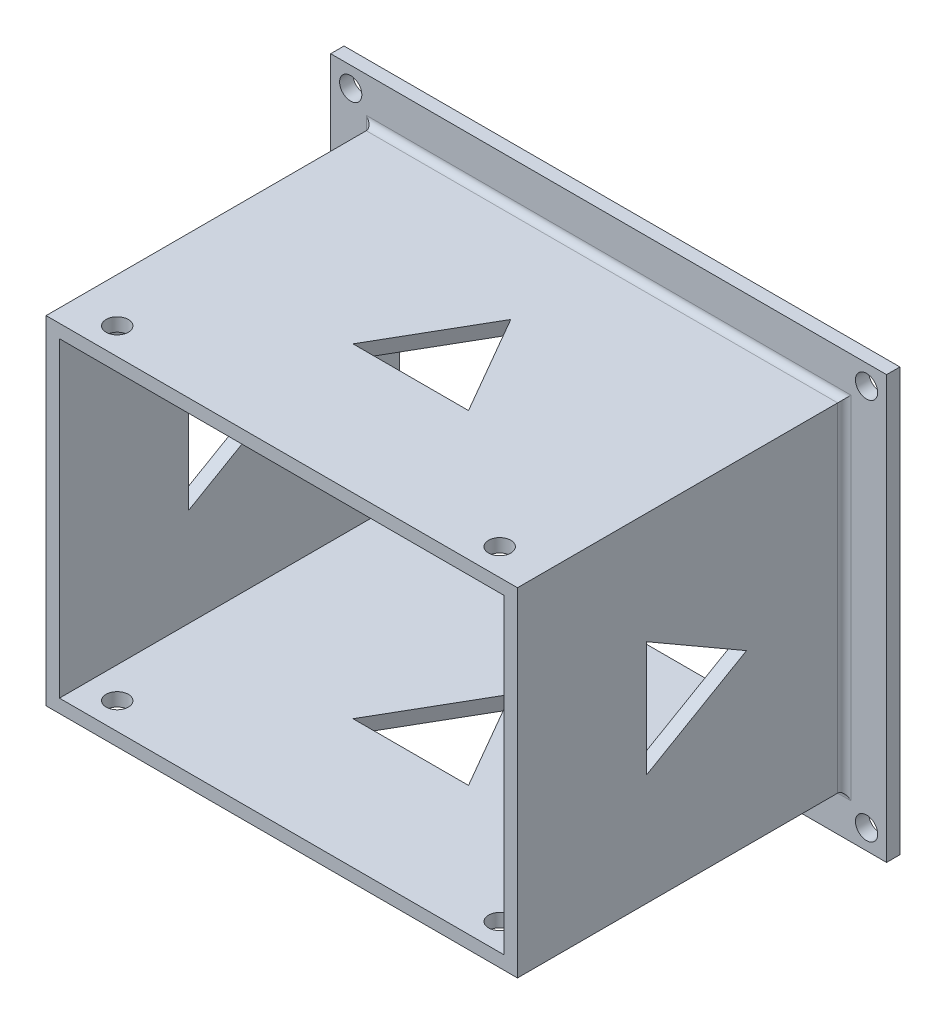
SolidWorks part; units mm, degrees
ref_plane "前视基准面" through (0, 0, 0) normal (0, 0, 1) x (1, 0, 0)
ref_plane "上视基准面" through (0, 0, 0) normal (0, 1, 0) x (1, 0, 0)
ref_plane "右视基准面" through (0, 0, 0) normal (1, 0, 0) x (0, 0, -1)
sketch "草图1" plane through (0, 0, 0) normal (0, 0, 1) x (1, 0, 0)
  line L1 (-62.5, 47.5) -> (62.5, 47.5)
  line L2 (-62.5, 47.5) -> (-62.5, -47.5)
  line L3 (-62.5, -47.5) -> (62.5, -47.5)
  line L4 (62.5, 47.5) -> (62.5, -47.5)
  line L5 (0, -47.5) -> (0, 47.5) construction
  line L6 (-62.5, 0) -> (62.5, 0) construction
  line L7 (-50, 35) -> (50, 35)
  line L8 (-50, 35) -> (-50, -35)
  line L9 (-50, -35) -> (50, -35)
  line L10 (50, 35) -> (50, -35)
  line L11 (0, -35) -> (0, 35) construction
  line L12 (-50, 0) -> (50, 0) construction
  point P0 (0, 0)
  point P4 (0, 0)
  dimension "D1" = 100
  dimension "D2" = 125
  dimension "D3" = 70
  dimension "D4" = 95
extrude "凸台-拉伸1" add sketch "草图1" along normal blind 3
sketch "草图2" plane through (0, 0, 3) normal (0, 0, 1) x (1, 0, 0)
  line L0 (50, -35) -> (50, 35) construction
  line L1 (-53, 38) -> (53, 38)
  line L2 (-53, 38) -> (-53, -38)
  line L3 (-53, -38) -> (53, -38)
  line L4 (53, 38) -> (53, -38)
  line L5 (0, -38) -> (0, 38) construction
  line L6 (-53, 0) -> (53, 0) construction
  line L7 (-50, -35) -> (50, -35) construction
  line L9 (-50, 35) -> (50, 35)
  line L10 (-50, 35) -> (-50, -35)
  line L11 (-50, -35) -> (50, -35)
  line L12 (50, 35) -> (50, -35)
  line L13 (0, -35) -> (0, 35) construction
  line L14 (-50, 0) -> (50, 0) construction
  point P0 (0, 0)
  point P8 (0, 0)
  dimension "D1" = 3
  dimension "D2" = 3
extrude "凸台-拉伸2" add sketch "草图2" along normal blind 73.5
sketch "草图3" plane through (0, -38, 0) normal (0, -1, 0) x (1, 0, 0)
  line L0 (-53, 76.5) -> (53, 76.5) construction
  line L1 (-53, 76.5) -> (-53, 3) construction
  line L2 (0, 0) -> (0, 28.9302) construction
  line L3 (-62.5, 0) -> (62.5, 0) construction
  circle A0 centre (-43, 70.5) radius 2.5
  circle A1 centre (43, 70.5) radius 2.5
  dimension "D3" = 5
  dimension "D1" = 6
  dimension "D2" = 10
extrude "切除-拉伸1" cut sketch "草图3" against normal blind 113.5
fillet "圆角1" radius 1.5 4 edges at (0, -38, 3) (-53, 0, 3) (0, 38, 3) (53, 0, 3)
sketch "草图4" plane through (0, 0, 3) normal (0, 0, 1) x (1, 0, 0)
  line L0 (0, 0) -> (0, 18.6703) construction
  line L1 (0, 0) -> (18.252, 0) construction
  line L2 (62.5, 47.5) -> (-62.5, 47.5) construction
  line L3 (-62.5, 47.5) -> (-62.5, -47.5) construction
  circle A0 centre (-58, 43) radius 2.5
  circle A1 centre (58, 43) radius 2.5
  circle A2 centre (58, -43) radius 2.5
  circle A3 centre (-58, -43) radius 2.5
  point P10 (-58.7259, 38.9073)
  dimension "D1" = 5
  dimension "D2" = 4.5
  dimension "D3" = 4.5
extrude "切除-拉伸2" cut sketch "草图4" against normal blind 113.5
sketch "草图5" plane through (0, -38, 0) normal (0, -1, 0) x (1, 0, 0)
  line L1 (0, 25) -> (12.9904, 47.5)
  line L2 (12.9904, 47.5) -> (-12.9904, 47.5)
  line L3 (-12.9904, 47.5) -> (0, 25)
  circle A0 centre (0, 40) radius 7.5 construction
  point P1 (0, 0)
  dimension "D1" = 15
  dimension "D2" = 40
extrude "切除-拉伸3" cut sketch "草图5" against normal blind 113.5
sketch "草图6" plane through (-53, 0, 0) normal (-1, 0, 0) x (0, 0, 1)
  line L1 (25, 0) -> (47.5, -12.9904)
  line L2 (47.5, -12.9904) -> (47.5, 12.9904)
  line L3 (47.5, 12.9904) -> (25, 0)
  circle A0 centre (40, 0) radius 7.5 construction
  point P1 (0, 0)
  dimension "D1" = 15
  dimension "D2" = 40
extrude "切除-拉伸4" cut sketch "草图6" against normal blind 113.5
